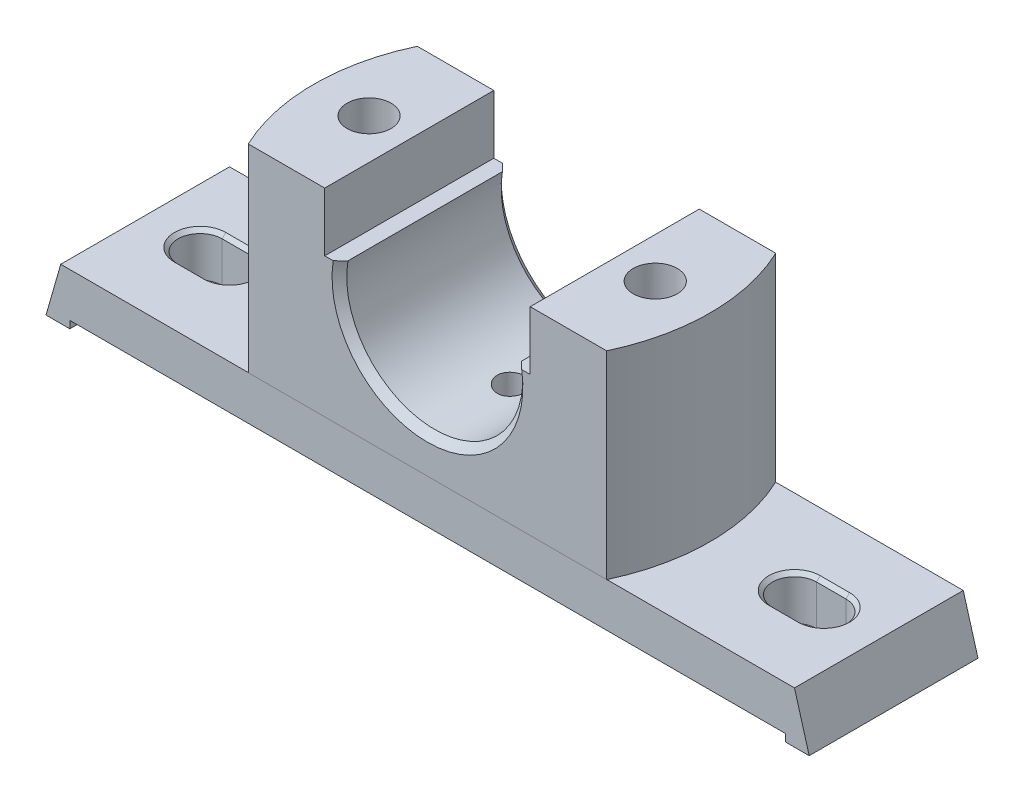
SolidWorks part; units mm, degrees
material "Gray Cast Iron"
ref_plane "Front Plane" through (0, 0, 0) normal (0, 0, 1) x (1, 0, 0)
ref_plane "Top Plane" through (0, 0, 0) normal (0, 1, 0) x (1, 0, 0)
ref_plane "Right Plane" through (0, 0, 0) normal (1, 0, 0) x (0, 0, -1)
sketch "Sketch1" plane through (0, 0, 0) normal (0, 0, 1) x (1, 0, 0)
  line L0 (0, 28.8041) -> (0, -28.8041) construction
  line L1 (104, 0) -> (97.5, 0)
  line L2 (-104, 0) -> (-99.9856, 14)
  line L3 (-99.9856, 14) -> (99.9856, 14)
  line L4 (97.5, 0) -> (97.5, 2)
  line L5 (104, 0) -> (99.9856, 14)
  line L6 (-97.5, 0) -> (-97.5, 2)
  line L11 (-97.5, 0) -> (-104, 0)
  line L13 (-97.5, 2) -> (97.5, 2)
  point P4 (0, 0)
  point P9 (0, 2)
  point P11 (0, 0)
  point P13 (0, 0)
  point P14 (0, 14)
  dimension "D1" = 104
  dimension "D2" = 97.5
  dimension "D3" = 106
  dimension "D4" = 2
  dimension "D5" = 14
extrude "Boss-Extrude1" add sketch "Sketch1" along normal mid plane 46
sketch "Sketch3" plane through (0, 14, 0) normal (0, 1, 0) x (1, 0, 0)
  line L0 (-99.9856, -23) -> (-99.9856, 23) construction
  line L1 (-48.8377, 23.0408) -> (48.8377, 23.0408)
  line L3 (-48.8377, -23.0408) -> (48.8377, -23.0408)
  arc A0 (-48.8377, 23.0408) -> (-48.8377, -23.0408) centre (0, 0) ccw
  arc A1 (48.8377, -23.0408) -> (48.8377, 23.0408) centre (0, 0) ccw
  dimension "D1" = 54
  dimension "D2" = 51.1479
extrude "Boss-Extrude2" add sketch "Sketch3" along normal blind 54
sketch "Sketch5" plane through (0, 68, 0) normal (0, 1, 0) x (1, 0, 0)
  circle A0 centre (0, 0) radius 4
  dimension "D1" = 8
extrude "Cut-Extrude1" cut sketch "Sketch5" against normal blind 52
sketch "Sketch6" plane through (0, 0, 23.0408) normal (0, 0, 1) x (1, 0, 0)
  line L0 (-48.8377, 68) -> (48.8377, 68) construction
  line L3 (-28, 68) -> (-28, 52)
  line L4 (-28, 52) -> (-23.6643, 52)
  line L5 (28, 68) -> (28, 52)
  line L6 (0, 52) -> (0, 68) construction
  line L7 (-28, 60) -> (28, 60) construction
  line L8 (23.6643, 52) -> (28, 52)
  line L10 (48.8377, 68) -> (48.8377, 14) construction
  arc A0 (-23.6643, 52) -> (23.6643, 52) centre (0, 48) ccw
  point P4 (0, 60)
  dimension "D1" = 48
  dimension "D2" = 20
  dimension "D3" = 56
  dimension "D4" = 16
  dimension "D5" = 20.8377
extrude "Cut-Extrude5" cut sketch "Sketch6" against normal through all flip side to cut
sketch "Sketch8" plane through (0, 68, 0) normal (0, 1, 0) x (1, 0, 0)
  line L0 (-28, 23.0408) -> (-48.8377, 23.0408) construction
  line L2 (0, 48.6905) -> (0, -48.6905) construction
  line L3 (-120.5721, 0) -> (120.5721, 0) construction
  circle A0 centre (-39, 0.0408) radius 6
  circle A1 centre (39, 0.0408) radius 6
  point P7 (0, 0)
  point P13 (0, 0)
  dimension "D1" = 12
  dimension "D2" = 39
  dimension "D5" = 39
  dimension "D4" = 12
  dimension "D3" = 23
extrude "Cut-Extrude6" cut sketch "Sketch8" against normal through all
sketch "Sketch9" plane through (0, 14, 0) normal (0, 1, 0) x (1, 0, 0)
  line L0 (-117.9342, 0) -> (117.9342, 0) construction
  line L1 (0, 54.4058) -> (0, -54.4058) construction
  line L2 (-85, 0) -> (-77, 0) construction
  line L3 (-85, 6) -> (-77, 6)
  line L4 (-85, -6) -> (-77, -6)
  line L5 (85, 0) -> (77, 0) construction
  line L6 (85, 6) -> (77, 6)
  line L7 (85, -6) -> (77, -6)
  arc A0 (-85, 6) -> (-85, -6) centre (-85, 0) ccw
  arc A1 (-77, -6) -> (-77, 6) centre (-77, 0) ccw
  arc A2 (85, 6) -> (85, -6) centre (85, 0) cw
  arc A3 (77, -6) -> (77, 6) centre (77, 0) cw
  point P5 (0, 0)
  point P9 (0, 0)
  point P11 (-81, 0)
  point P18 (81, 0)
  dimension "D2" = 6
  dimension "D1" = 8
  dimension "D3" = 77
extrude "Cut-Extrude7" cut sketch "Sketch9" against normal through all
sketch "Sketch10" plane through (0, 2, 0) normal (0, -1, 0) x (-1, 0, 0)
  line L0 (0, -52.2076) -> (0, 52.2076) construction
  line L1 (53, -13.9592) -> (25, -13.9592)
  line L2 (53, -13.9592) -> (53, 14.0408)
  line L3 (53, 14.0408) -> (25, 14.0408)
  line L4 (25, -13.9592) -> (25, 14.0408)
  line L5 (39, 14.0408) -> (39, -13.9592) construction
  line L6 (53, 0.0408) -> (25, 0.0408) construction
  line L7 (-53, 14.0408) -> (-25, 14.0408)
  line L8 (-25, -13.9592) -> (-25, 14.0408)
  line L9 (-53, -13.9592) -> (-25, -13.9592)
  line L10 (-53, -13.9592) -> (-53, 14.0408)
  point P0 (39, 0.0408)
  point P7 (0, 0)
  dimension "D1" = 28
  dimension "D2" = 28
extrude "Cut-Extrude8" cut sketch "Sketch10" against normal blind 10
chamfer "Chamfer1" distance 2 angle 45 2 edges at (0, 24, -23.0408) (0, 24, 23.0408)
chamfer "Chamfer2" distance 1 angle 45 8 edges at (81, 14, 6) (91, 14, 0) (71, 14, 0) (81, 14, -6) (-81, 14, 6) (-71, 14, 0) (-91, 14, 0) (-81, 14, -6)
